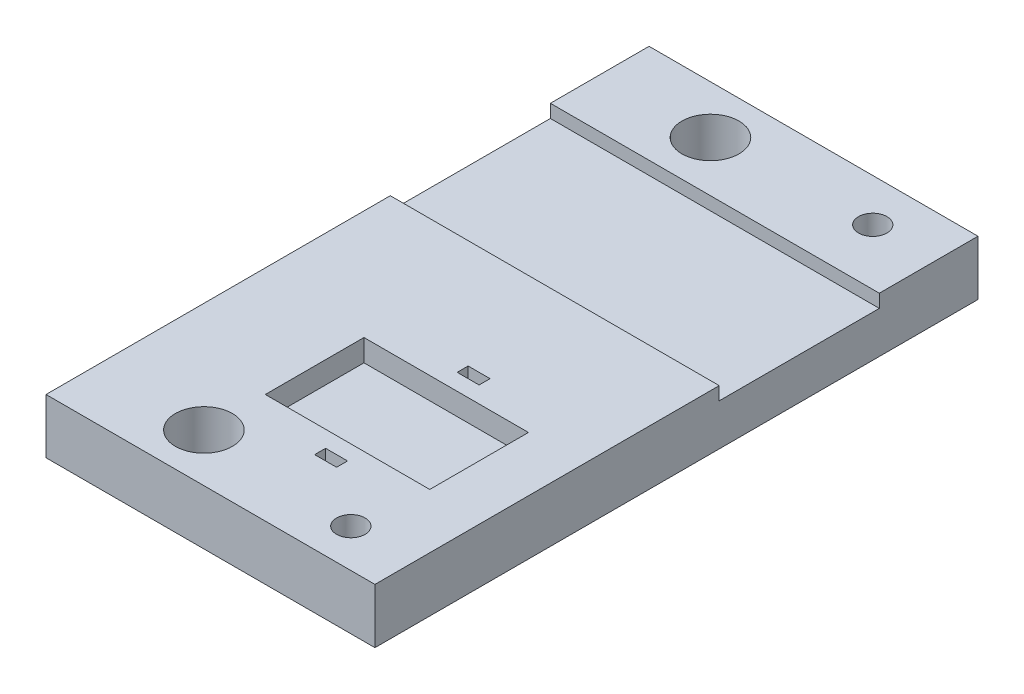
SolidWorks part; units mm, degrees
ref_plane "Front Plane" through (0, 0, 0) normal (0, 0, 1) x (1, 0, 0)
ref_plane "Top Plane" through (0, 0, 0) normal (0, 1, 0) x (1, 0, 0)
ref_plane "Right Plane" through (0, 0, 0) normal (1, 0, 0) x (0, 0, -1)
sketch "Sketch1" plane through (0, 0, 0) normal (0, 1, 0) x (1, 0, 0)
  line L1 (0, 0) -> (25.4, 0) construction
  line L2 (0, 0) -> (0, 58.674) construction
  line L3 (0, 58.674) -> (25.4, 58.674) construction
  line L4 (25.4, 0) -> (25.4, 58.674) construction
  line L5 (-12.7, 64.262) -> (25.4, 64.262)
  line L6 (-12.7, 64.262) -> (-12.7, -5.588)
  line L7 (-12.7, -5.588) -> (25.4, -5.588)
  line L8 (25.4, 64.262) -> (25.4, -5.588)
  circle A0 centre (0, 0) radius 3.302
  circle A1 centre (0, 58.674) radius 3.302
  circle A2 centre (18.161, 59.309) radius 1.651
  circle A3 centre (18.161, -1.143) radius 1.651
  dimension "D1" = 6.604
  dimension "D3" = 6.604
  dimension "D8" = 3.302
  dimension "D9" = 7.239
  dimension "D2" = 58.674
  dimension "D4" = 25.4
  dimension "D5" = 69.85
  dimension "D6" = 5.588
  dimension "D7" = 38.1
  dimension "D10" = 4.953
  dimension "D11" = 2
extrude "Boss-Extrude1" add sketch "Sketch1" along normal blind 6.35
sketch "Sketch2" plane through (0, 6.35, 0) normal (0, 1, 0) x (1, 0, 0)
  line L6 (-12.7, 64.262) -> (25.4, 64.262) construction
  line L7 (0, 18.542) -> (19.05, 18.542)
  line L8 (0, 18.542) -> (0, 7.112)
  line L9 (0, 7.112) -> (19.05, 7.112)
  line L10 (19.05, 18.542) -> (19.05, 7.112)
  line L11 (25.4, 64.262) -> (25.4, -5.588) construction
  dimension "D1" = 11.43
  dimension "D2" = 19.05
  dimension "D3" = 45.72
  dimension "D4" = 6.35
extrude "Cut-Extrude1" cut sketch "Sketch2" against normal blind 2.54
sketch "Sketch5" plane through (0, 6.35, 0) normal (0, 1, 0) x (1, 0, 0)
  line L0 (19.05, 18.542) -> (0, 18.542) construction
  line L1 (8.89, 20.447) -> (11.43, 20.447)
  line L2 (8.89, 20.447) -> (8.89, 21.717)
  line L3 (8.89, 21.717) -> (11.43, 21.717)
  line L4 (11.43, 20.447) -> (11.43, 21.717)
  line L5 (19.05, 7.112) -> (19.05, 18.542) construction
  line L6 (8.89, 3.937) -> (8.89, 5.207)
  line L7 (8.89, 3.937) -> (11.43, 3.937)
  line L8 (11.43, 3.937) -> (11.43, 5.207)
  line L9 (8.89, 5.207) -> (11.43, 5.207)
  dimension "D1" = 2.54
  dimension "D2" = 1.27
  dimension "D3" = 1.905
  dimension "D4" = 7.62
  dimension "D5" = 2
extrude "Cut-Extrude2" cut sketch "Sketch5" against normal through all both and the other way through all
sketch "Sketch6" plane through (0, 0, 0) normal (0, -1, 0) x (1, 0, 0)
  line L1 (8.89, -5.207) -> (11.43, -5.207)
  line L2 (8.89, -5.207) -> (8.89, -20.447)
  line L3 (8.89, -20.447) -> (11.43, -20.447)
  line L4 (11.43, -5.207) -> (11.43, -20.447)
extrude "Cut-Extrude3" cut sketch "Sketch6" against normal blind 1.016
sketch "Sketch7" plane through (0, 6.35, 0) normal (0, 1, 0) x (1, 0, 0)
  line L0 (25.4, 64.262) -> (25.4, -5.588) construction
  line L1 (-12.7, 52.832) -> (25.4, 52.832)
  line L2 (-12.7, 52.832) -> (-12.7, 34.29)
  line L3 (-12.7, 34.29) -> (25.4, 34.29)
  line L4 (25.4, 52.832) -> (25.4, 34.29)
  line L5 (-12.7, 64.262) -> (-12.7, -5.588) construction
  line L6 (-12.7, 64.262) -> (25.4, 64.262) construction
  dimension "D1" = 18.542
  dimension "D2" = 11.43
extrude "Cut-Extrude4" cut sketch "Sketch7" against normal blind 1.524
